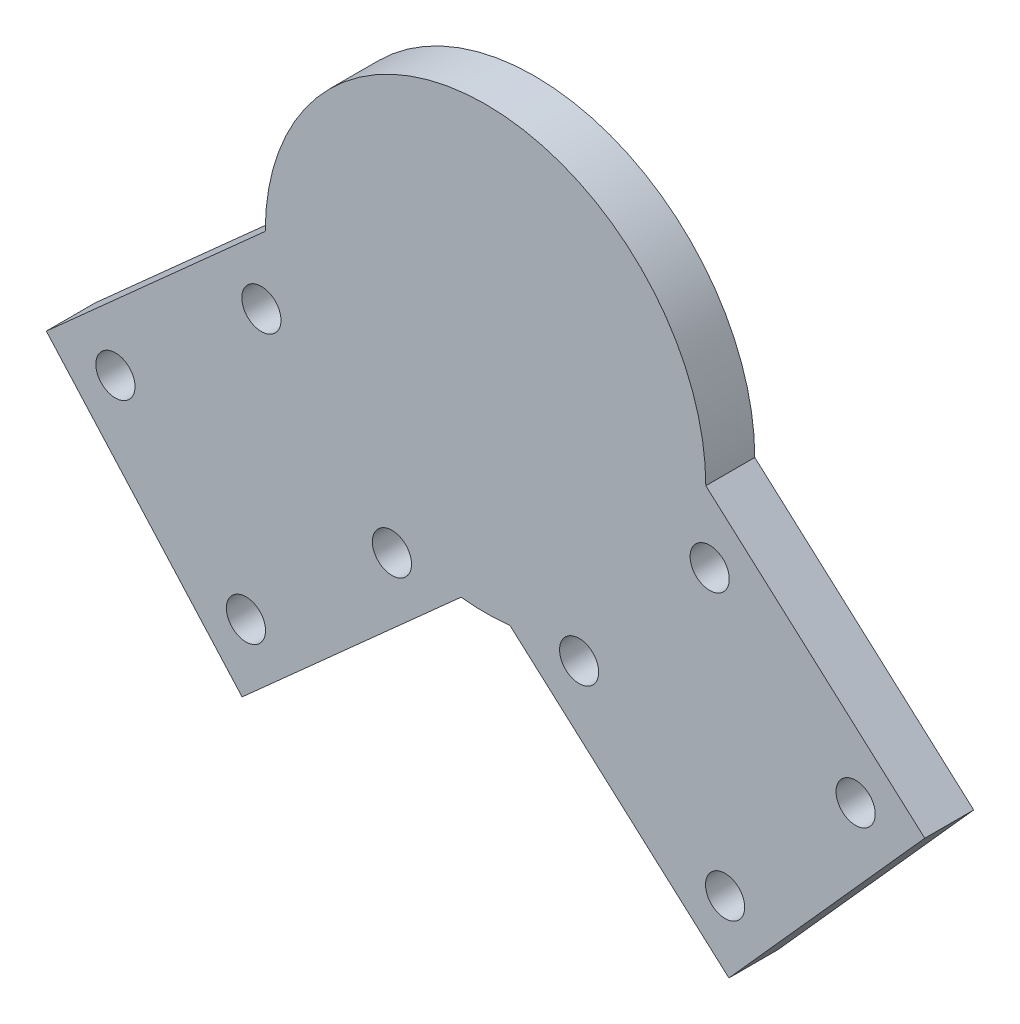
SolidWorks part; units mm, degrees
ref_plane "Front Plane" through (0, 0, 0) normal (0, 0, 1) x (1, 0, 0)
ref_plane "Top Plane" through (0, 0, 0) normal (0, 1, 0) x (1, 0, 0)
ref_plane "Right Plane" through (0, 0, 0) normal (1, 0, 0) x (0, 0, -1)
sketch "Sketch2" plane through (0, 0, 0) normal (0, 0, 1) x (1, 0, 0)
  line L0 (-22.5, 0) -> (-2.5, -22.3607)
  line L1 (-22.5, 0) -> (-44.8607, -20)
  line L2 (-2.5, -22.3607) -> (-24.8607, -42.3607)
  line L3 (-44.8607, -20) -> (-24.8607, -42.3607)
  line L4 (2.5, -22.3607) -> (22.5, 0)
  line L5 (2.5, -22.3607) -> (24.8607, -42.3607)
  line L6 (22.5, 0) -> (44.8607, -20)
  line L7 (24.8607, -42.3607) -> (44.8607, -20)
  line L8 (-22.5, 0) -> (0, 0)
  line L9 (0, 0) -> (-2.5, -22.3607)
  line L10 (2.5, -22.3607) -> (0, 0)
  line L11 (22.5, 0) -> (0, 0)
  circle A0 centre (0, 0) radius 22.5
  dimension "D5" = 45
  dimension "D1" = 30
  dimension "D2" = 30
  dimension "D3" = 30
  dimension "D4" = 30
extrude "Boss-Extrude1" add sketch "Sketch2" along normal blind 5 contours L0 L1 L3 L2 | L4 L5 L7 L6 | A0
sketch "Sketch3" plane through (0, 0, 0) normal (0, 0, -1) x (-1, 0, 0)
  line L0 (2.5, -22.3607) -> (24.8607, -42.3607) construction
  line L1 (44.8607, -20) -> (24.8607, -42.3607) construction
  line L2 (-22.5, 0) -> (-44.8607, -20) construction
  line L3 (-24.8607, -42.3607) -> (-44.8607, -20) construction
  line L4 (-22.5, 0) -> (-2.5, -22.3607)
  line L5 (-2.5, -22.3607) -> (-24.8607, -42.3607) construction
  line L6 (-37.8006, -20.3934) -> (-22.8934, -7.0601)
  line L7 (-22.8934, -7.0601) -> (-9.5601, -21.9672)
  line L8 (-9.5601, -21.9672) -> (-24.4672, -35.3006)
  line L9 (-37.8006, -20.3934) -> (-24.4672, -35.3006)
  line L10 (22.5, 0) -> (44.8607, -20) construction
  line L11 (24.4672, -35.3006) -> (37.8006, -20.3934)
  line L12 (37.8006, -20.3934) -> (22.8934, -7.0601)
  line L13 (22.8934, -7.0601) -> (9.5601, -21.9672)
  line L14 (9.5601, -21.9672) -> (24.4672, -35.3006)
  circle A0 centre (-37.8006, -20.3934) radius 2
  circle A1 centre (-22.8934, -7.0601) radius 2
  circle A2 centre (-9.5601, -21.9672) radius 2
  circle A3 centre (-24.4672, -35.3006) radius 2
  circle A4 centre (24.4672, -35.3006) radius 2
  circle A5 centre (37.8006, -20.3934) radius 2
  circle A6 centre (9.5601, -21.9672) radius 2
  circle A7 centre (22.8934, -7.0601) radius 2
  dimension "D3" = 4
  dimension "D7" = 4
  dimension "D8" = 4
  dimension "D9" = 4
  dimension "D12" = 4
  dimension "D15" = 4
  dimension "D16" = 4
  dimension "D17" = 4
  dimension "D1" = 5
  dimension "D2" = 5
  dimension "D4" = 30
  dimension "D5" = 5
  dimension "D6" = 5
  dimension "D10" = 5
  dimension "D11" = 5
  dimension "D13" = 5
  dimension "D14" = 5
extrude "Cut-Extrude1" cut sketch "Sketch3" against normal blind 5 from surface at 0 contours A1 | A0 | A3 | A2 | A6 | A7 | A5 | A4 starting at face at (0, -18.3853, 0)
